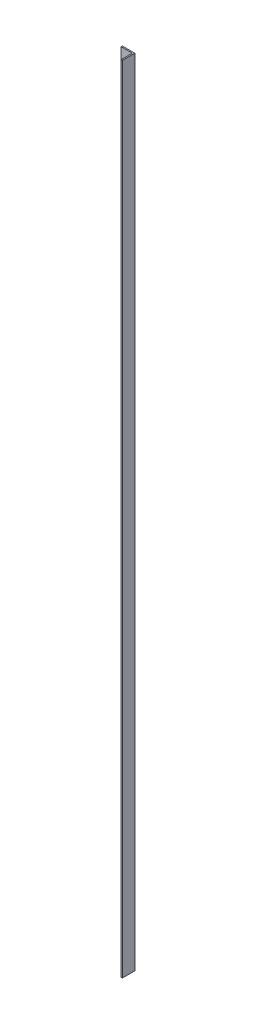
SolidWorks part; units mm, degrees
material "1.0114 (S235J0)"
ref_plane "Спереди" through (0, 0, 0) normal (0, 0, 1) x (1, 0, 0)
ref_plane "Сверху" through (0, 0, 0) normal (0, 1, 0) x (1, 0, 0)
ref_plane "Справа" through (0, 0, 0) normal (1, 0, 0) x (0, 0, -1)
sketch "Эскиз1" plane through (0, 0, 0) normal (0, 0, 1) x (1, 0, 0)
  line L1 (-492.5, 2893.75) -> (-447.5, 2893.75)
  line L2 (-492.5, 2893.75) -> (-492.5, -306.25)
  line L3 (-492.5, -306.25) -> (-447.5, -306.25)
  line L4 (-447.5, 2893.75) -> (-447.5, -306.25)
  dimension "D1" = 45
  dimension "D2" = 3200
extrude "Бобышка-Вытянуть1" add sketch "Эскиз1" along normal blind 5
sketch "Эскиз3" plane through (0, 2893.75, 0) normal (0, 1, 0) x (1, 0, 0)
  line L0 (-447.5, 0) -> (-442.5, 0)
  line L1 (-442.5, 0) -> (-442.5, -5)
  line L2 (-442.5, -5) -> (-442.5, -50)
  line L3 (-442.5, -50) -> (-447.5, -50)
  line L4 (-447.5, -50) -> (-447.5, 0)
extrude "Бобышка-Вытянуть3" add sketch "Эскиз3" against normal blind 3200
